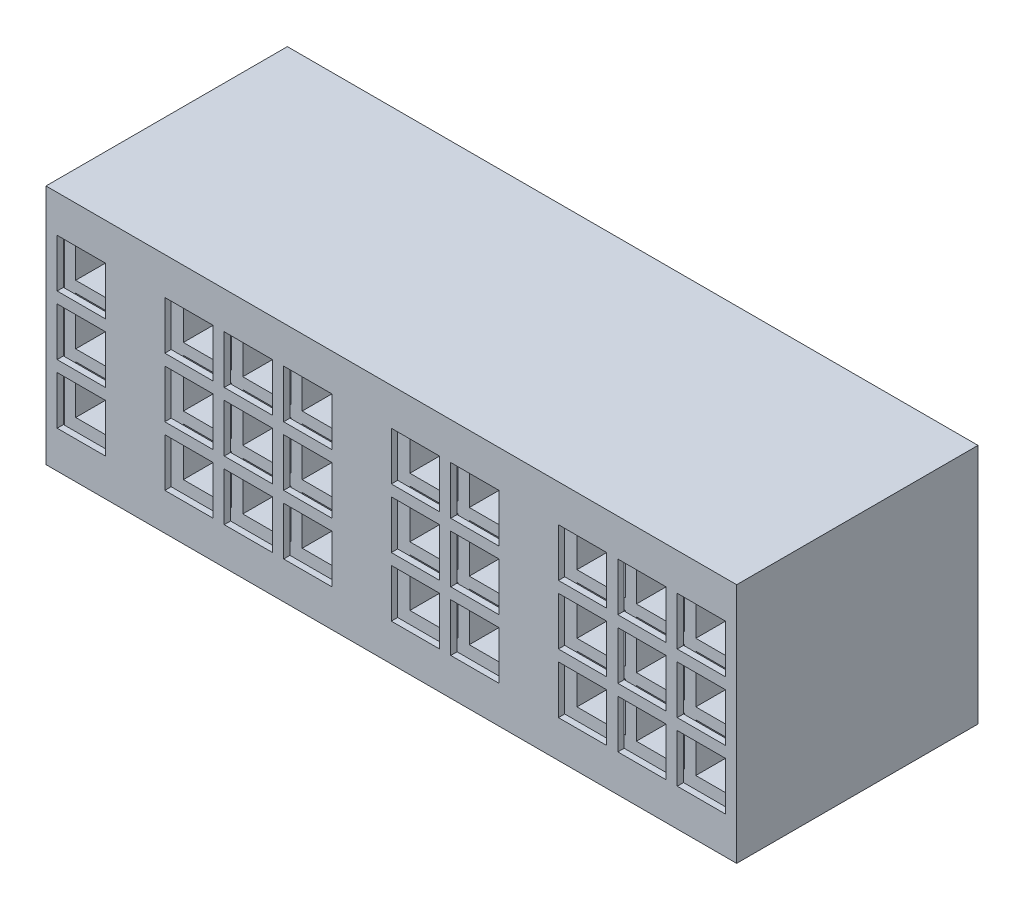
SolidWorks part; units mm, degrees
ref_plane "Plan de face" through (0, 0, 0) normal (0, 0, 1) x (1, 0, 0)
ref_plane "Plan de dessus" through (0, 0, 0) normal (0, 1, 0) x (1, 0, 0)
ref_plane "Plan de droite" through (0, 0, 0) normal (1, 0, 0) x (0, 0, -1)
sketch "Esquisse1" plane through (0, 0, 0) normal (0, 0, 1) x (1, 0, 0)
  line L1 (-93, -51) -> (93, -51)
  line L2 (-93, -51) -> (-93, 0)
  line L3 (-93, 0) -> (93, 0)
  line L4 (93, -51) -> (93, 0)
  line L13 (0, 49979.1071) -> (0, -49979.1071) construction
  point P0 (0, 0)
  point P16 (0, -51)
  point P17 (0, 0)
  point P27 (0, 0)
  dimension "D1" = 186
  dimension "D2" = 51
extrude "Boss.-Extru.1" add sketch "Esquisse1" along normal blind 35
sketch "Esquisse7" plane through (0, 0, 35) normal (0, 0, 1) x (1, 0, 0)
  line L0 (93, 0) -> (-93, 0) construction
  line L1 (-90, -3) -> (-77, -3)
  line L2 (-90, -3) -> (-90, -16)
  line L3 (-90, -16) -> (-77, -16)
  line L4 (-77, -3) -> (-77, -16)
  line L5 (-90, -3) -> (-77, -16) construction
  line L6 (-90, -16) -> (-77, -3) construction
  line L7 (-93, 0) -> (-93, -51) construction
  point P0 (-83.5, -9.5)
  dimension "D1" = 13
  dimension "D2" = 13
  dimension "D3" = 3
  dimension "D4" = 3
extrude "Enlèv. mat.-Extru.5" cut sketch "Esquisse7" against normal blind 91
pattern_linear "Répétition linéaire5" count 3 spacing 16 along (0, -1, 0) of "Enlèv. mat.-Extru.5"
sketch "Esquisse8" plane through (0, 0, 35) normal (0, 0, 1) x (1, 0, 0)
  line L0 (93, 0) -> (-93, 0) construction
  line L1 (-61, -3) -> (-48, -3)
  line L2 (-61, -3) -> (-61, -16)
  line L3 (-61, -16) -> (-48, -16)
  line L4 (-48, -3) -> (-48, -16)
  line L5 (-61, -3) -> (-48, -16) construction
  line L6 (-61, -16) -> (-48, -3) construction
  line L7 (-77, -16) -> (-77, -3) construction
  point P0 (-54.5, -9.5)
  dimension "D1" = 13
  dimension "D2" = 13
  dimension "D3" = 3
  dimension "D4" = 16
extrude "Enlèv. mat.-Extru.6" cut sketch "Esquisse8" against normal blind 103
pattern_linear "Répétition linéaire6" count 3 spacing 16 along (0, -1, 0) count 3 spacing 16 along (1, 0, 0) of "Enlèv. mat.-Extru.6"
sketch "Esquisse9" plane through (0, 0, 35) normal (0, 0, 1) x (1, 0, 0)
  line L0 (-16, -16) -> (-16, -3) construction
  line L1 (0, -3) -> (13, -3)
  line L2 (0, -3) -> (0, -16)
  line L3 (0, -16) -> (13, -16)
  line L4 (13, -3) -> (13, -16)
  line L5 (0, -3) -> (13, -16) construction
  line L6 (0, -16) -> (13, -3) construction
  line L7 (93, 0) -> (-93, 0) construction
  point P0 (6.5, -9.5)
  dimension "D1" = 13
  dimension "D2" = 13
  dimension "D3" = 16
  dimension "D4" = 3
extrude "Enlèv. mat.-Extru.7" cut sketch "Esquisse9" against normal blind 77
pattern_linear "Répétition linéaire7" count 3 spacing 16 along (0, -1, 0) count 2 spacing 16 along (1, 0, 0) of "Enlèv. mat.-Extru.7"
sketch "Esquisse10" plane through (0, 0, 35) normal (0, 0, 1) x (1, 0, 0)
  line L0 (29, -16) -> (29, -3) construction
  line L1 (45, -3) -> (58, -3)
  line L2 (45, -3) -> (45, -16)
  line L3 (45, -16) -> (58, -16)
  line L4 (58, -3) -> (58, -16)
  line L5 (45, -3) -> (58, -16) construction
  line L6 (45, -16) -> (58, -3) construction
  line L7 (93, 0) -> (-93, 0) construction
  point P0 (51.5, -9.5)
  dimension "D1" = 13
  dimension "D2" = 13
  dimension "D3" = 16
  dimension "D4" = 3
extrude "Enlèv. mat.-Extru.8" cut sketch "Esquisse10" against normal blind 78
pattern_linear "Répétition linéaire8" count 3 spacing 16 along (1, 0, 0) count 3 spacing 16 along (0, -1, 0) of "Enlèv. mat.-Extru.8"
sketch "Esquisse14" plane through (0, -51, 0) normal (0, -1, 0) x (1, 0, 0)
  line L0 (0, 0) -> (-15.3262, 0) construction
  line L1 (-12.6631, 0) -> (-2.6631, 0)
  line L2 (-12.6631, 0) -> (-12.6631, 5)
  line L3 (-12.6631, 5) -> (-2.6631, 5)
  line L4 (-2.6631, 0) -> (-2.6631, 5)
  line L5 (-12.6631, 0) -> (-2.6631, 5) construction
  line L6 (-12.6631, 5) -> (-2.6631, 0) construction
  line L7 (-93, 0) -> (93, 0) construction
  point P0 (-7.6631, 2.5)
  point P5 (-15.3262, 0)
  point P6 (0, 0)
  point P10 (0, 0)
  point P12 (-7.6631, 0)
  point P13 (-7.6631, 0)
  dimension "D1" = 10
  dimension "D2" = 5
extrude "Boss.-Extru.3" add sketch "Esquisse14" along normal blind 7
sketch "Esquisse25" plane through (0, 0, 0) normal (0, 1, 0) x (1, 0, 0)
  line L1 (-93, 0) -> (93, 0)
  line L2 (-93, 0) -> (-93, -35)
  line L3 (-93, -35) -> (93, -35)
  line L4 (93, 0) -> (93, -35)
extrude "Boss.-Extru.7" add sketch "Esquisse25" along normal blind 7
sketch "Esquisse18" plane through (0, -51, 0) normal (0, -1, 0) x (1, 0, 0)
  line L0 (-93, 0) -> (93, 0)
  line L2 (93, 0) -> (93, 35)
  line L3 (93, 35) -> (-93, 35)
  line L4 (-93, 35) -> (-93, 0)
extrude "Boss.-Extru.5" add sketch "Esquisse18" along normal blind 7
sketch "Esquisse16" plane through (-93, 0, 0) normal (-1, 0, 0) x (0, 0, 1)
  line L0 (35, -58) -> (0, -58) construction
  line L3 (33.3, -53) -> (30, -53)
  line L4 (30, -53) -> (30, 2)
  line L5 (30, 2) -> (33.3, 2)
  line L6 (33.3, 2) -> (33.3, -53)
  line L8 (0, 7) -> (35, 7) construction
  point P0 (0, 0)
  point P1 (31.65, -53)
  point P13 (0, 0)
  dimension "D1" = 5
  dimension "D4" = 5
  dimension "D5" = 3.3
extrude "Enlèv. mat.-Extru.11" cut sketch "Esquisse16" against normal blind 184
sketch "Esquisse15" plane through (0, 0, 0) normal (0, 0, -1) x (-1, 0, 0)
  circle A0 centre (8.4823, -42.4466) radius 1
  circle A1 centre (8.4823, -9.749) radius 1
  circle A2 centre (68.823, -42.4466) radius 1
  circle A3 centre (68.823, -9.749) radius 1
  circle A4 centre (-37.1355, -42.4466) radius 1
  circle A5 centre (-39.2159, -11.2606) radius 1
  dimension "D1" = 2
  dimension "D2" = 2
  dimension "D3" = 2
  dimension "D4" = 2
  dimension "D5" = 2
  dimension "D6" = 2
extrude "Enlèv. mat.-Extru.10" cut sketch "Esquisse15" against normal blind 7
sketch "Esquisse24" plane through (0, 0, 0) normal (0, 0, -1) x (-1, 0, 0)
  line L0 (77, -48) -> (90, -48) construction
  line L1 (88.5, -48) -> (78.5, -48)
  line L2 (88.5, -48) -> (88.5, -50)
  line L3 (88.5, -50) -> (78.5, -50)
  line L4 (78.5, -48) -> (78.5, -50)
  line L5 (48, -48) -> (61, -48) construction
  line L6 (59.5, -48) -> (49.5, -48)
  line L7 (59.5, -48) -> (59.5, -50)
  line L8 (59.5, -50) -> (49.5, -50)
  line L9 (49.5, -48) -> (49.5, -50)
  line L10 (32, -48) -> (45, -48) construction
  line L11 (43.5, -48) -> (33.5, -48)
  line L12 (43.5, -48) -> (43.5, -50)
  line L13 (43.5, -50) -> (33.5, -50)
  line L14 (33.5, -48) -> (33.5, -50)
  line L15 (16, -48) -> (29, -48) construction
  line L16 (27.5, -48) -> (17.5, -48)
  line L17 (27.5, -48) -> (27.5, -50)
  line L18 (27.5, -50) -> (17.5, -50)
  line L19 (17.5, -48) -> (17.5, -50)
  line L20 (-13, -48) -> (0, -48) construction
  line L21 (-1.5, -48) -> (-11.5, -48)
  line L22 (-1.5, -48) -> (-1.5, -50)
  line L23 (-1.5, -50) -> (-11.5, -50)
  line L24 (-11.5, -48) -> (-11.5, -50)
  line L25 (-29, -48) -> (-16, -48) construction
  line L26 (-17.5, -48) -> (-27.5, -48)
  line L27 (-17.5, -48) -> (-17.5, -50)
  line L28 (-17.5, -50) -> (-27.5, -50)
  line L29 (-27.5, -48) -> (-27.5, -50)
  line L30 (-58, -48) -> (-45, -48) construction
  line L31 (-46.5, -48) -> (-56.5, -48)
  line L32 (-46.5, -48) -> (-46.5, -50)
  line L33 (-46.5, -50) -> (-56.5, -50)
  line L34 (-56.5, -48) -> (-56.5, -50)
  line L35 (-74, -48) -> (-61, -48) construction
  line L36 (-62.5, -48) -> (-72.5, -48)
  line L37 (-62.5, -48) -> (-62.5, -50)
  line L38 (-62.5, -50) -> (-72.5, -50)
  line L39 (-72.5, -48) -> (-72.5, -50)
  line L40 (-90, -48) -> (-77, -48) construction
  line L41 (-78.5, -48) -> (-88.5, -48)
  line L42 (-78.5, -48) -> (-78.5, -50)
  line L43 (-78.5, -50) -> (-88.5, -50)
  line L44 (-88.5, -48) -> (-88.5, -50)
  line L45 (-77, -3) -> (-90, -3) construction
  line L46 (-78.5, -3) -> (-88.5, -3)
  line L47 (-78.5, -3) -> (-78.5, -1)
  line L48 (-78.5, -1) -> (-88.5, -1)
  line L49 (-88.5, -3) -> (-88.5, -1)
  line L50 (-61, -3) -> (-74, -3) construction
  line L51 (-62.5, -3) -> (-72.5, -3)
  line L52 (-62.5, -3) -> (-62.5, -1)
  line L53 (-62.5, -1) -> (-72.5, -1)
  line L54 (-72.5, -3) -> (-72.5, -1)
  line L55 (-45, -3) -> (-58, -3) construction
  line L56 (-46.5, -3) -> (-56.5, -3)
  line L57 (-46.5, -3) -> (-46.5, -1)
  line L58 (-46.5, -1) -> (-56.5, -1)
  line L59 (-56.5, -3) -> (-56.5, -1)
  line L60 (-16, -3) -> (-29, -3) construction
  line L61 (-17.5, -3) -> (-27.5, -3)
  line L62 (-17.5, -3) -> (-17.5, -1)
  line L63 (-17.5, -1) -> (-27.5, -1)
  line L64 (-27.5, -3) -> (-27.5, -1)
  line L65 (0, -3) -> (-13, -3) construction
  line L66 (-1.5, -3) -> (-11.5, -3)
  line L67 (-1.5, -3) -> (-1.5, -1)
  line L68 (-1.5, -1) -> (-11.5, -1)
  line L69 (-11.5, -3) -> (-11.5, -1)
  line L70 (29, -3) -> (16, -3) construction
  line L71 (17.5, -3) -> (27.5, -3)
  line L72 (17.5, -3) -> (17.5, -1)
  line L73 (17.5, -1) -> (27.5, -1)
  line L74 (27.5, -3) -> (27.5, -1)
  line L75 (45, -3) -> (32, -3) construction
  line L76 (33.5, -3) -> (43.5, -3)
  line L77 (33.5, -3) -> (33.5, -1)
  line L78 (33.5, -1) -> (43.5, -1)
  line L79 (43.5, -3) -> (43.5, -1)
  line L80 (61, -3) -> (48, -3) construction
  line L81 (49.5, -3) -> (59.5, -3)
  line L82 (49.5, -3) -> (49.5, -1)
  line L83 (49.5, -1) -> (59.5, -1)
  line L84 (59.5, -3) -> (59.5, -1)
  line L85 (90, -3) -> (77, -3) construction
  line L86 (78.5, -3) -> (88.5, -3)
  line L87 (78.5, -3) -> (78.5, -1)
  line L88 (78.5, -1) -> (88.5, -1)
  line L89 (88.5, -3) -> (88.5, -1)
  point P108 (83.5, -48)
  point P109 (54.5, -48)
  point P110 (38.5, -48)
  point P111 (22.5, -48)
  point P112 (-6.5, -48)
  point P113 (-22.5, -48)
  point P114 (-51.5, -48)
  point P115 (-67.5, -48)
  point P116 (-83.5, -48)
  point P117 (-83.5, -3)
  point P118 (-67.5, -3)
  point P119 (-51.5, -3)
  point P120 (-22.5, -3)
  point P121 (-6.5, -3)
  point P122 (22.5, -3)
  point P123 (38.5, -3)
  point P124 (54.5, -3)
  point P125 (83.5, -3)
  point P126 (83.5, -3)
  point P127 (0, 0)
  point P128 (54.5, -3)
  point P129 (0, 0)
  point P130 (38.5, -3)
  point P131 (0, 0)
  point P132 (22.5, -3)
  point P133 (0, 0)
  point P134 (-6.5, -3)
  point P135 (0, 0)
  point P136 (-22.5, -3)
  point P137 (0, 0)
  point P138 (-51.5, -3)
  point P139 (0, 0)
  point P140 (-67.5, -3)
  point P141 (0, 0)
  point P142 (0, 0)
  point P143 (-83.5, -3)
  point P144 (0, 0)
  point P145 (-83.5, -48)
  point P146 (0, 0)
  point P147 (0, 0)
  point P148 (-51.5, -48)
  point P149 (0, 0)
  point P150 (-22.5, -48)
  point P151 (0, 0)
  point P152 (-6.5, -48)
  point P153 (0, 0)
  point P154 (22.5, -48)
  point P155 (0, 0)
  point P156 (38.5, -48)
  point P157 (0, 0)
  point P158 (0, 0)
  point P159 (54.5, -48)
  point P160 (0, 0)
  point P161 (83.5, -48)
  dimension "D1" = 10
  dimension "D2" = 10
  dimension "D3" = 10
  dimension "D4" = 10
  dimension "D5" = 10
  dimension "D6" = 10
  dimension "D7" = 10
  dimension "D8" = 10
  dimension "D9" = 10
  dimension "D10" = 10
  dimension "D11" = 10
  dimension "D12" = 10
  dimension "D13" = 10
  dimension "D14" = 10
  dimension "D15" = 10
  dimension "D16" = 10
  dimension "D17" = 10
  dimension "D18" = 10
  dimension "D19" = 2
  dimension "D20" = 2
  dimension "D21" = 2
  dimension "D22" = 2
  dimension "D23" = 2
  dimension "D24" = 2
  dimension "D25" = 2
  dimension "D26" = 2
  dimension "D27" = 2
  dimension "D28" = 2
  dimension "D29" = 2
  dimension "D30" = 2
  dimension "D31" = 2
  dimension "D32" = 2
  dimension "D33" = 2
  dimension "D34" = 2
  dimension "D35" = 2
  dimension "D36" = 2
extrude "Enlèv. mat.-Extru.12" cut sketch "Esquisse24" against normal blind 1
sketch "Esquisse19" plane through (0, 0, 0) normal (0, 0, -1) x (-1, 0, 0)
  line L0 (-93, -58) -> (-93, 7) construction
  line L1 (93, -58) -> (-93, -58)
  line L2 (93, -58) -> (93, -57)
  line L3 (93, -57) -> (-93, -57)
  line L4 (-93, -58) -> (-93, -57)
  line L5 (93, 7) -> (93, -58) construction
  line L6 (-93, 7) -> (93, 7)
  line L7 (-93, 7) -> (-93, 6)
  line L8 (-93, 6) -> (93, 6)
  line L9 (93, 7) -> (93, 6)
  line L11 (-93, -57) -> (-92, -57)
  line L12 (-93, -57) -> (-93, 6)
  line L13 (-93, 6) -> (-92, 6)
  line L14 (-92, -57) -> (-92, 6)
  line L15 (93, 6) -> (92, 6)
  line L16 (93, 6) -> (93, -57)
  line L17 (93, -57) -> (92, -57)
  line L18 (92, 6) -> (92, -57)
  dimension "D1" = 1
  dimension "D2" = 1
  dimension "D3" = 1
  dimension "D4" = 1
extrude "Boss.-Extru.8" add sketch "Esquisse19" along normal blind 30 contours L4 L1 L2 L3 | L8 L18 L3 L16 | L9 L6 L7 L8 | L3 L14 L8 L12
sketch "Esquisse26" plane through (-93, 0, 0) normal (-1, 0, 0) x (0, 0, 1)
  line L0 (-30, -58) -> (2.5, 7) construction
  line L1 (-30, 7) -> (35, 7) construction
  line L2 (-30, 7) -> (2.5, -58) construction
  line L3 (35, -58) -> (-30, -58) construction
  circle A0 centre (-13.75, -25.5) radius 1.75
  dimension "D1" = 3.5
extrude "Enlèv. mat.-Extru.14" cut sketch "Esquisse26" against normal blind 30
